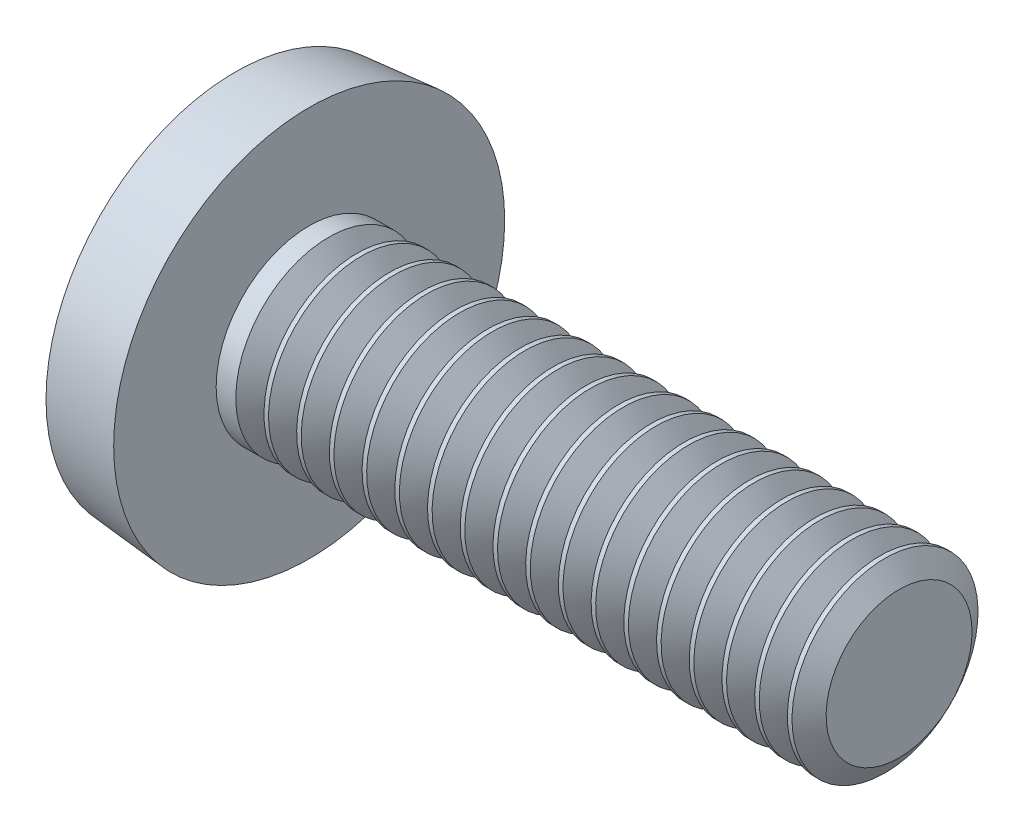
SolidWorks part; units mm, degrees
ref_plane "Plane1" through (0, 0, 0) normal (0, 0, 1) x (1, 0, 0)
ref_plane "Plane2" through (0, 0, 0) normal (0, 1, 0) x (1, 0, 0)
ref_plane "Plane3" through (0, 0, 0) normal (1, 0, 0) x (0, 0, -1)
other "Configuration Table"
sketch "BodySke" plane through (0, 0, 0) normal (0, 0, 1) x (1, 0, 0)
  line L0 (2.2098, 1.7526) -> (2.2098, 3.683)
  line L1 (2.2098, 3.683) -> (0.8128, 3.5608)
  line L2 (-25.4, 0) -> (127, 0) construction
  line L3 (2.2098, -3.683) -> (0.8128, -3.5608) construction
  line L4 (2.2098, 1.7526) -> (13.3223, 1.7526)
  line L5 (13.3223, 1.7526) -> (13.3223, 0)
  line L6 (13.3223, 0) -> (0, 0)
  line L7 (2.2098, -1.7526) -> (13.3223, -1.7526) construction
  line L8 (2.8448, 6.35) -> (2.8448, -3.175) construction
  line L9 (2.2098, 6.35) -> (2.2098, -3.175) construction
  arc A0 (0, 0) -> (0.8128, 3.5608) centre (8.2061, 0) cw
  dimension "Head_ang" = 85
  dimension "Oval_ht" = 0.8128
  dimension "Head_ht" = 2.2098
  dimension "Diameter" = 3.5052
  dimension "Length" = 11.1125
  dimension "Head_dia" = 7.366
  dimension "Advance" = 0.635
  dimension "Thread_nom" = 11.1125
revolve "Base-Revolve" add sketch "BodySke" angle 360 about L2
cosmetic thread "ThreadCosmetic" [suppressed] parameters "Thread_length"=10.4775, "Thread_minor"=2.7483
sketch "Sketch2" plane through (0, 0, 0) normal (1, 0, 0) x (0, 0, -1)
  line L0 (3.683, -0.6096) -> (3.683, 0.6096)
  line L1 (3.683, 0.6096) -> (-3.683, 0.6096)
  line L2 (-3.683, 0.6096) -> (-3.683, -0.6096)
  line L3 (-3.683, -0.6096) -> (3.683, -0.6096)
  dimension "D1" = 7.366
  dimension "D2" = 3.683
  dimension "D3" = 0.6096
  dimension "Slot_width" = 1.2192
extrude "Slot" [suppressed] cut sketch "Sketch2" along normal blind 1.3462
sketch "Sketch3" plane through (0, 0, 0) normal (1, 0, 0) x (0, 0, -1)
  line L0 (-0.4953, 2.413) -> (0.4953, 2.413)
  line L1 (0.4953, 2.413) -> (0.4953, -2.413)
  line L2 (0.4953, -2.413) -> (-0.4953, -2.413)
  line L3 (-0.4953, -2.413) -> (-0.4953, 2.413)
  dimension "Cross_width" = 0.9906
  dimension "D1" = 0.4953
  dimension "Cross_dia" = 4.826
  dimension "D2" = 2.413
ref_plane "Plane4" through (2.794, 0, 0) normal (1, 0, 0) x (0, 0, -1)
sketch "Sketch4" plane through (2.794, 0, 0) normal (1, 0, 0) x (0, 0, -1)
  line L0 (-0.2476, 0.2476) -> (0.2477, 0.2477)
  line L1 (0.2477, 0.2477) -> (0.2477, -0.2477)
  line L2 (0.2477, -0.2477) -> (-0.2476, -0.2477)
  line L3 (-0.2476, -0.2477) -> (-0.2476, 0.2476)
  dimension "D1" = 0.4953
  dimension "D2" = 0.2476
  dimension "D3" = 0.4953
  dimension "D4" = 0.2476
loft "Cross" cut profiles "Sketch3", "Sketch4"
pattern_circular "CirPattern1" count 2 every 90 about axis through (0, 0, 0) along (1, 0, 0) of "Cross"
sketch "ThdSchSke" plane through (0, 0, 0) normal (0, 0, 1) x (1, 0, 0)
  line L0 (2.8448, -1.3741) -> (2.5798, -1.7526)
  line L1 (2.8448, -1.3741) -> (3.1098, -1.7526)
  line L2 (3.1098, -1.7526) -> (3.1098, -2.1908)
  line L3 (-3.175, 0) -> (5.1513, 0) construction
  line L5 (3.1098, -2.1908) -> (2.5798, -2.1908)
  line L6 (2.5798, -2.1908) -> (2.5798, -1.7526)
  dimension "Diameter" = 3.5052
  dimension "SideAngle" = 55
  dimension "VeeAngle" = 70
  dimension "Thread_minor" = 2.7483
  dimension "Overcut" = 4.3815
  dimension "Start" = 2.8448
revolve "ThreadSchematic" cut sketch "ThdSchSke" angle 360 about L3
pattern_linear "ThdSchPat" count 18 spacing 0.6163 along (1, 0, 0) of "ThreadSchematic"
equation "\"D1@Sketch3\" = \"Cross_width@Sketch3\" / 2"
equation "\"D2@Sketch3\" = \"Cross_dia@Sketch3\" / 2"
equation "\"D1@Sketch4\" = \"Cross_width@Sketch3\"*.5"
equation "\"D2@Sketch4\" = \"D1@Sketch4\" / 2"
equation "\"D3@Sketch4\" = \"D1@Sketch4\""
equation "\"D4@Sketch4\" = \"D2@Sketch4\""
equation "\"D1@Sketch2\" = \"Head_dia@BodySke\""
equation "\"D2@Sketch2\" = \"D1@Sketch2\" / 2"
equation "\"D3@Sketch2\" = \"Slot_width@Sketch2\" / 2"
equation "\"Thread_length@ThreadCosmetic\" = ((sgn( (\"Length@BodySke\" - \"Advance@BodySke\" ) - \"Thread_nom@BodySke\" )-1)*( (\"Length@BodySke\" - \"Advance@BodySke\" ) - \"Thread_nom@BodySke\" ))/-2+ \"Thread_nom@BodySke\""
equation "\"Thread_minor@ThdSchSke\" = \"Thread_minor@ThreadCosmetic\""
equation "\"Diameter@ThdSchSke\" = \"Diameter@BodySke\""
equation "\"Overcut@ThdSchSke\" = \"Diameter@BodySke\" * 1.25"
equation "\"Start@ThdSchSke\" = \"Head_ht@BodySke\" + \"Length@BodySke\" - \"Thread_length@ThreadCosmetic\"  '---Non-countersunk---"
equation "\"Num_threads@ThdSchPat\" = int( \"Thread_length@ThreadCosmetic\" / \"Advance@BodySke\" + 0.999 )  + 1"
equation "\"Advance@ThdSchPat\" = \"Thread_length@ThreadCosmetic\" /  (\"Num_threads@ThdSchPat\" - 1) 'relax it"
